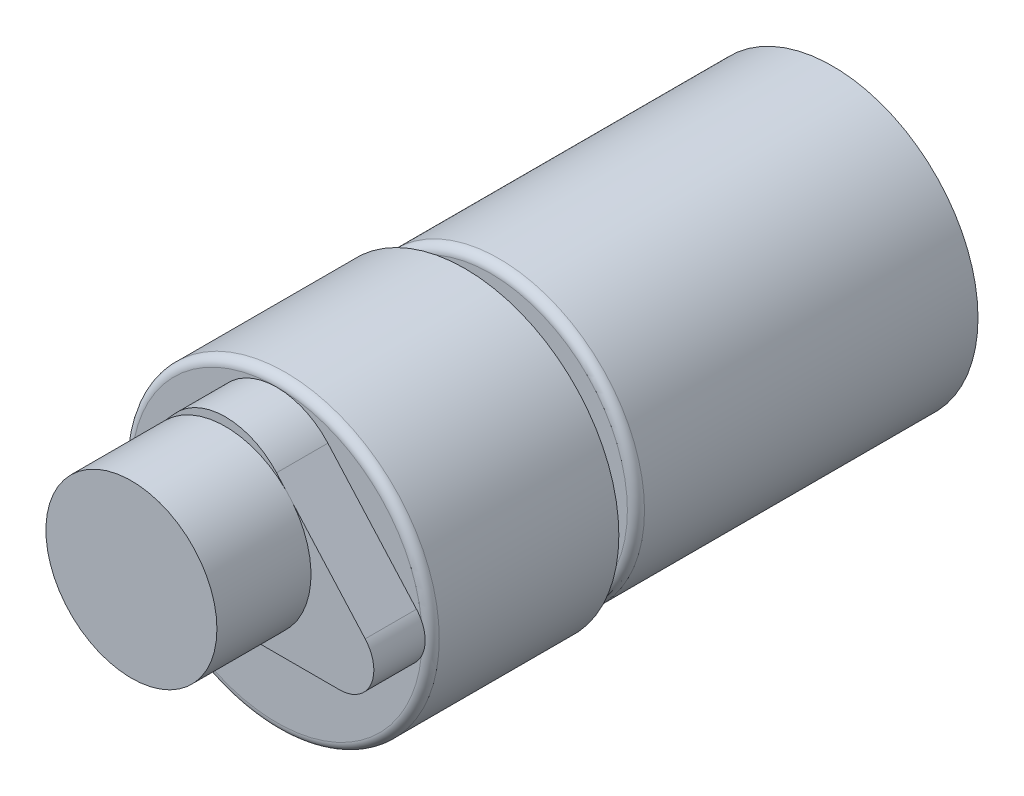
SolidWorks part; units mm, degrees
ref_plane "Front Plane" through (0, 0, 0) normal (0, 0, 1) x (1, 0, 0)
ref_plane "Top Plane" through (0, 0, 0) normal (0, 1, 0) x (1, 0, 0)
ref_plane "Right Plane" through (0, 0, 0) normal (1, 0, 0) x (0, 0, -1)
sketch "Esquisse1" plane through (0, 0, 0) normal (0, 0, 1) x (1, 0, 0)
  circle A0 centre (0, 0) radius 17
  dimension "D1" = 34
extrude "Boss.-Extru.1" add sketch "Esquisse1" along normal blind 40
ref_plane "Plan1" through (0, 0, 40) normal (0, 0, 1) x (1, 0, 0)
sketch "Esquisse2" plane through (0, 0, 40) normal (0, 0, 1) x (1, 0, 0)
  circle A0 centre (0, 0) radius 5
  dimension "D1" = 10
extrude "Boss.-Extru.2" add sketch "Esquisse2" along normal blind 3
fillet "Congé1" radius 1 1 edges at (17, 0, 40)
ref_plane "Plan3" through (0, 0, 43) normal (0, 0, 1) x (1, 0, 0)
sketch "Esquisse3" plane through (0, 0, 43) normal (0, 0, 1) x (1, 0, 0)
  circle A0 centre (0, 0) radius 18
  dimension "D1" = 36
extrude "Boss.-Extru.3" add sketch "Esquisse3" along normal blind 22
fillet "Congé2" radius 1 1 edges at (18, 0, 65)
ref_plane "Plan4" through (0, 0, 65) normal (0, 0, 1) x (1, 0, 0)
sketch "Esquisse4" plane through (0, 0, 65) normal (0, 0, 1) x (1, 0, 0)
  line L0 (-13.3502, -4) -> (13.3502, -4)
  line L1 (16.3369, 2.6607) -> (5.9736, 14.2943)
  line L2 (-5.9736, 14.2943) -> (-16.3369, 2.6607)
  arc A0 (5.9736, 14.2943) -> (-5.9736, 14.2943) centre (0, 8.9729) ccw
  arc A2 (13.3502, -4) -> (16.3369, 2.6607) centre (13.3502, 0) ccw
  arc A3 (-13.3502, -4) -> (-16.3369, 2.6607) centre (-13.3502, 0) cw
  point P6 (0, 21)
  point P7 (0, 0)
  point P9 (0, 16.9729)
  point P11 (22.2704, -4)
  point P14 (-22.2704, -4)
  point P15 (-17, -1.6367)
  point P16 (17, -1.6367)
  point P17 (14.0947, -2.4119)
  point P18 (-14.1434, -2.3165)
  dimension "D6" = 8
  dimension "D7" = 4
  dimension "D1" = 4
  dimension "D2" = 34
  dimension "D3" = 17
  dimension "D4" = 0
  dimension "D5" = 25
extrude "Boss.-Extru.4" add sketch "Esquisse4" along normal blind 6
ref_plane "Plan5" through (0, 0, 71) normal (0, 0, 1) x (1, 0, 0)
sketch "Esquisse5" plane through (0, 0, 71) normal (0, 0, 1) x (1, 0, 0)
  circle A0 centre (0, 6) radius 10
  dimension "D1" = 20
  dimension "D2" = 0
  dimension "D3" = 6
extrude "Boss.-Extru.5" add sketch "Esquisse5" along normal blind 11 contours A0
